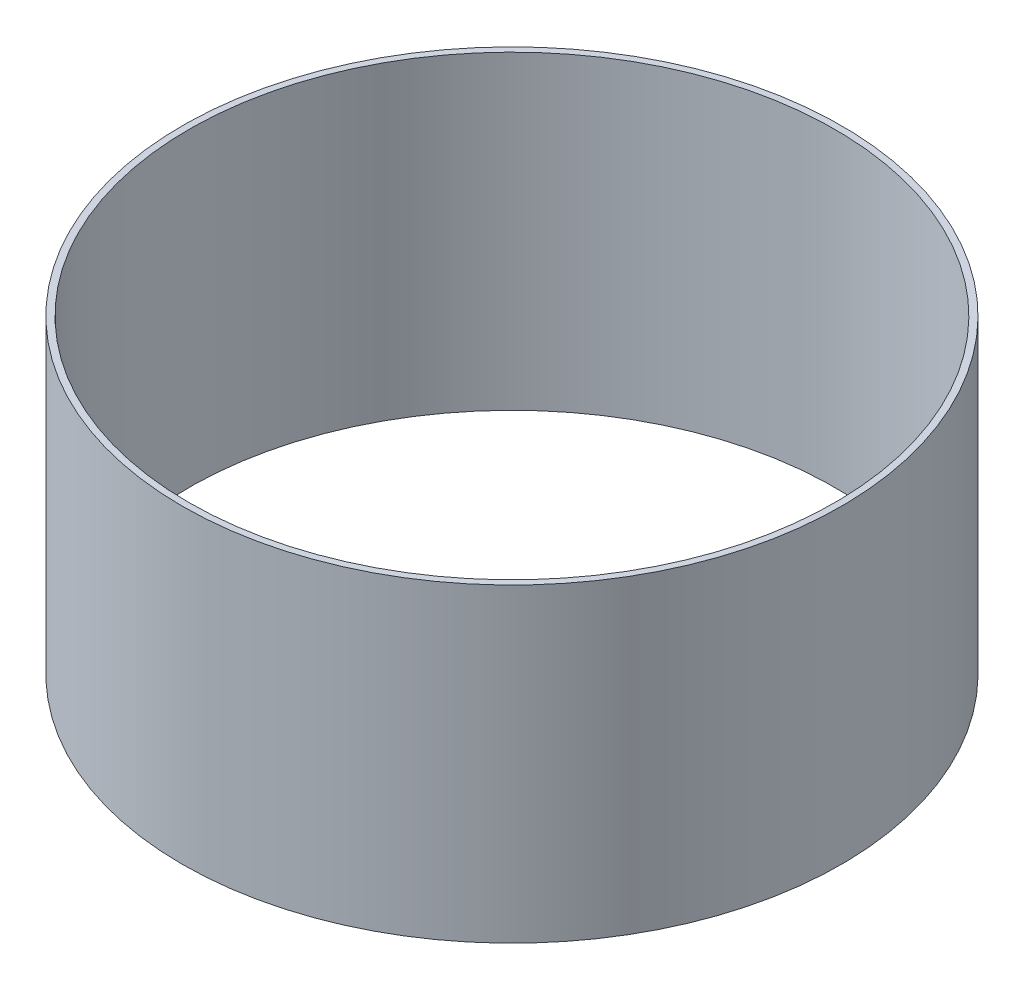
SolidWorks part; units mm, degrees
ref_plane "Спереди" through (0, 0, 0) normal (0, 0, 1) x (1, 0, 0)
ref_plane "Сверху" through (0, 0, 0) normal (0, 1, 0) x (1, 0, 0)
ref_plane "Справа" through (0, 0, 0) normal (1, 0, 0) x (0, 0, -1)
other "Configuration Table"
sketch "Эскиз1" plane through (0, 0, 0) normal (0, 1, 0) x (1, 0, 0)
  circle A0 centre (0, 0) radius 102
  circle A1 centre (0, 0) radius 100
  dimension "D1" = 204
  dimension "D2" = 200
extrude "Бобышка-Вытянуть1" add sketch "Эскиз1" against normal blind 96
